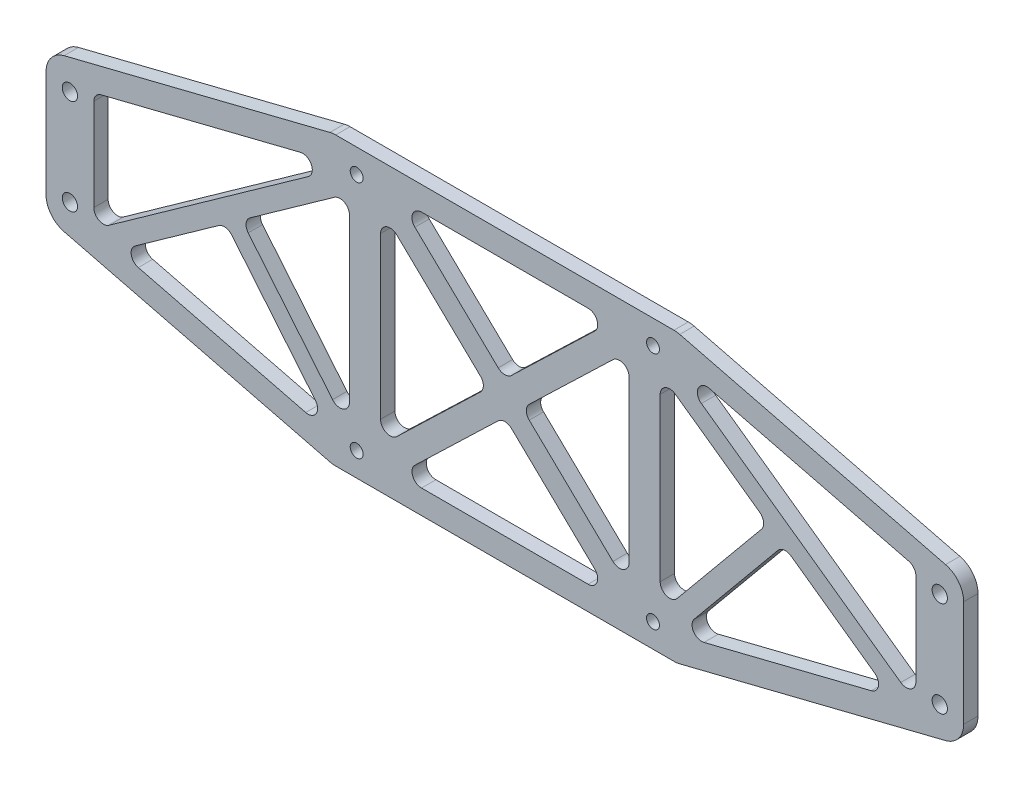
SolidWorks part; units mm, degrees
material "Thornel Mat VMA"
ref_plane "前视基准面" through (0, 0, 0) normal (0, 0, 1) x (1, 0, 0)
ref_plane "上视基准面" through (0, 0, 0) normal (0, 1, 0) x (1, 0, 0)
ref_plane "右视基准面" through (0, 0, 0) normal (1, 0, 0) x (0, 0, -1)
sketch "草图1" plane through (0, 0, 0) normal (0, 0, 1) x (1, 0, 0)
  line L1 (-101, -30) -> (101, -30)
  line L2 (-101, -30) -> (-101, 30)
  line L3 (-101, 30) -> (101, 30)
  line L4 (101, -30) -> (101, 30)
  line L5 (-101, -30) -> (101, 30) construction
  line L6 (-101, 30) -> (101, -30) construction
  line L7 (-31, -25) -> (31, -25) construction
  line L8 (-31, -25) -> (-31, 25) construction
  line L9 (-31, 25) -> (31, 25) construction
  line L10 (31, -25) -> (31, 25) construction
  line L11 (-31, -25) -> (31, 25) construction
  line L12 (-31, 25) -> (31, -25) construction
  circle A0 centre (31, 25) radius 1.35
  circle A1 centre (-31, 25) radius 1.35
  circle A2 centre (-31, -25) radius 1.35
  circle A3 centre (31, -25) radius 1.35
  point P0 (0, 0)
  point P6 (0, 0)
  dimension "D5" = 2.7
  dimension "D1" = 202
  dimension "D2" = 60
  dimension "D3" = 50
  dimension "D4" = 62
extrude "凸台-拉伸1" add sketch "草图1" along normal blind 3
sketch "草图2" plane through (0, 0, 3) normal (0, 0, 1) x (1, 0, 0)
  line L0 (91, 30) -> (91, -30) construction
  line L1 (101, 30) -> (-101, 30) construction
  line L2 (-101, -30) -> (101, -30) construction
  line L3 (101, -30) -> (101, 30) construction
  line L4 (0, 0) -> (91, 0) construction
  circle A0 centre (91, -10) radius 1.6
  circle A1 centre (91, 10) radius 1.6
  dimension "D2" = 3.2
  dimension "D1" = 10
  dimension "D3" = 20
extrude "切除-拉伸1" cut sketch "草图2" against normal blind 10
mirror "镜向1" about plane through (0, 0, 0) normal (1, 0, 0) of "切除-拉伸1"
sketch "草图3" plane through (0, 0, 3) normal (0, 0, 1) x (1, 0, 0)
  line L0 (-96, 15) -> (-96, -15)
  line L1 (-96, 15) -> (-36, 30)
  line L2 (101, 30) -> (-101, 30) construction
  line L3 (-96, 0) -> (0, 0) construction
  line L4 (0, 0) -> (0, 30) construction
  line L5 (96, 15) -> (36, 30)
  line L6 (96, 15) -> (96, -15)
  line L7 (-96, -15) -> (-36, -30)
  line L8 (96, -15) -> (36, -30)
  line L9 (-36, 30) -> (36, 30)
  line L10 (-36, -30) -> (36, -30)
  circle A0 centre (-31, 25) radius 1.35 construction
  circle A1 centre (-91, 10) radius 1.6 construction
  point P18 (96, 0)
  dimension "D1" = 5
  dimension "D2" = 5
  dimension "D3" = 5
extrude "切除-拉伸2" cut sketch "草图3" against normal blind 10 flip side to cut
sketch "草图4" plane through (0, 0, 3) normal (0, 0, 1) x (1, 0, 0)
  line L0 (-86, 12.3461) -> (-86, -12.3461)
  line L1 (-86, -12.3461) -> (-32.5, -25.7211)
  line L2 (-32.5, -25.7211) -> (-32.5, 25.7211)
  line L3 (-32.5, 25.7211) -> (-86, 12.3461)
  line L4 (-36, 30) -> (-96, 15) construction
  line L5 (-96, 15) -> (-96, -15) construction
  line L6 (-96, -15) -> (-36, -30) construction
  line L7 (-86, -12.3461) -> (-32.5, 25.7211)
  line L8 (-59.25, 6.6875) -> (-32.5, -25.7211) construction
  line L9 (-83.681, -15.6053) -> (-30.181, 22.462)
  line L10 (-60.7924, 5.4144) -> (-34.0424, -26.9942)
  line L11 (-57.7076, 7.9606) -> (-30.9576, -24.448)
  circle A0 centre (-91, 10) radius 1.6 construction
  circle A1 centre (-31, 25) radius 1.35 construction
  dimension "D1" = 5
  dimension "D2" = 5
  dimension "D3" = 5
  dimension "D4" = 1.5
  dimension "D5" = 4
  dimension "D6" = 2
  dimension "D7" = 2
extrude "切除-拉伸3" cut sketch "草图4" against normal blind 10
mirror "镜向2" about plane through (0, 0, 0) normal (1, 0, 0) of "切除-拉伸3"
sketch "草图6" plane through (0, 0, 3) normal (0, 0, 1) x (1, 0, 0)
  line L0 (36, 30) -> (-36, 30) construction
  line L1 (-26, -25) -> (26, -25)
  line L2 (-26, -25) -> (-26, 25)
  line L3 (-26, 25) -> (26, 25)
  line L4 (26, -25) -> (26, 25)
  line L5 (-26, -25) -> (26, 25) construction
  line L6 (-26, 25) -> (26, -25) construction
  line L7 (-27.7328, 23.1979) -> (24.2672, -26.8021)
  line L8 (-24.2672, -26.8021) -> (27.7328, 23.1979)
  line L9 (-24.2672, 26.8021) -> (27.7328, -23.1979)
  line L10 (-27.7328, -23.1979) -> (24.2672, 26.8021)
  circle A0 centre (-31, 25) radius 1.35 construction
  point P0 (0, 0)
  dimension "D1" = 5
  dimension "D2" = 5
  dimension "D3" = 2.5
  dimension "D4" = 2.5
extrude "切除-拉伸4" cut sketch "草图6" against normal blind 10 contours L2 L10 L7 | L9 L10 L3 | L8 L9 L4 | L8 L1 L7
fillet "圆角1" radius 2 30 edges at (26, -21.5318, 1.5) (3.6069, 0, 1.5) (26, 21.5318, 1.5) (22.3931, -25, 1.5) (-22.3931, -25, 1.5) (0, -3.4682, 1.5) (-3.6069, 0, 1.5) (-26, -21.5318, 1.5) (-26, 21.5318, 1.5) (86, 12.3461, 1.5) (86, -12.3461, 1.5) (32.5, 25.7211, 1.5) (-32.5, -22.5793, 1.5) (-55.0634, 4.7572, 1.5) (-32.5, 20.8119, 1.5) (-58.331, 2.4322, 1.5) (-86, -12.3461, 1.5) (-86, 12.3461, 1.5) (-32.5, 25.7211, 1.5) (58.331, 2.4322, 1.5) (80.8944, -13.6225, 1.5) (35.7675, -24.9042, 1.5) (55.0634, 4.7572, 1.5) (32.5, -22.5793, 1.5) (32.5, 20.8119, 1.5) (-22.3931, 25, 1.5) (22.3931, 25, 1.5) (0, 3.4682, 1.5) (-80.8944, -13.6225, 1.5) (-35.7675, -24.9042, 1.5)
fillet "圆角2" radius 5 8 edges at (-36, 30, 1.5) (-36, -30, 1.5) (36, -30, 1.5) (96, -15, 1.5) (96, 15, 1.5) (36, 30, 1.5) (-96, 15, 1.5) (-96, -15, 1.5)
